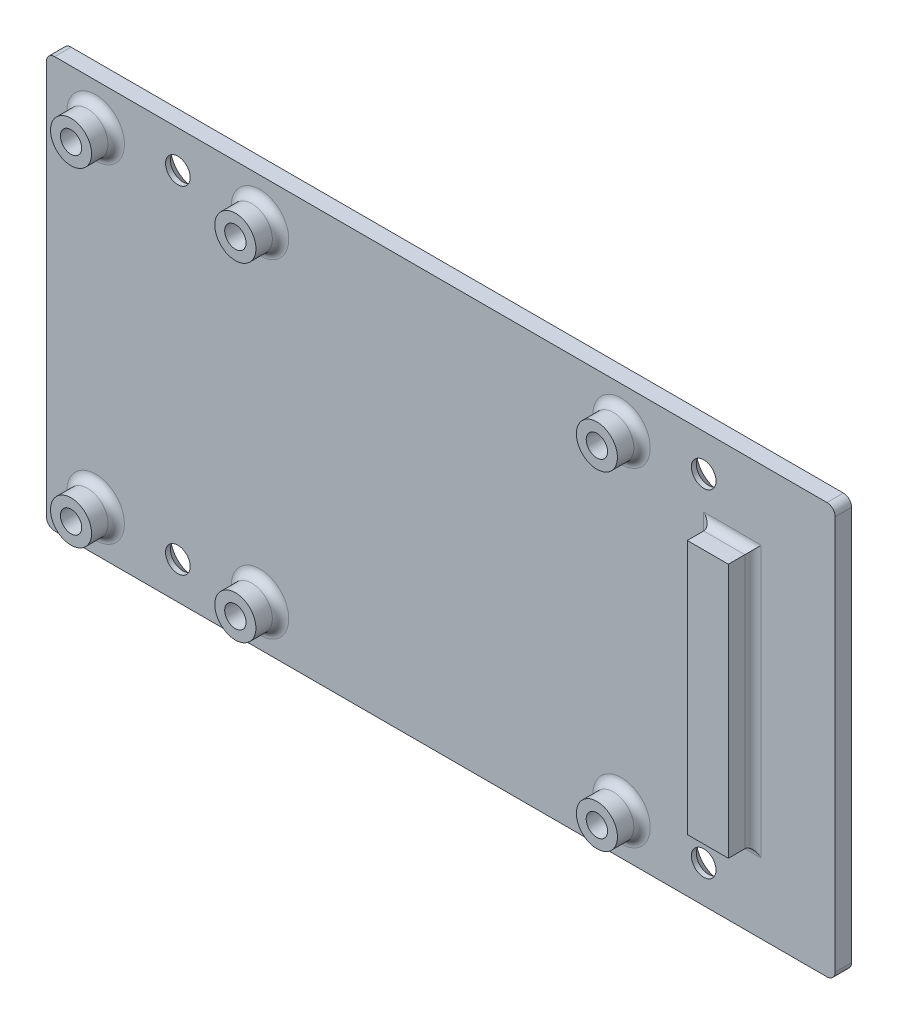
SolidWorks part; units mm, degrees
ref_plane "Спереди" through (0, 0, 0) normal (0, 0, 1) x (1, 0, 0)
ref_plane "Сверху" through (0, 0, 0) normal (0, 1, 0) x (1, 0, 0)
ref_plane "Справа" through (0, 0, 0) normal (1, 0, 0) x (0, 0, -1)
sketch "Эскиз1" plane through (0, 0, 60.7538) normal (0, 0, -1) x (-1, 0, 0)
  line L0 (-84.5501, 64.5438) -> (-84.5501, 29.5438)
  line L17 (-1.5112, 29.1447) -> (-7.5891, 29.1447)
  line L18 (-9.3198, 24.0438) -> (-63.7804, 24.0438)
  line L19 (-73.3198, 24.0438) -> (-82.5501, 24.0438)
  line L20 (-82.5501, 24.0438) -> (-82.5501, 29.5438)
  line L21 (-82.5501, 29.5438) -> (-84.5501, 29.5438)
  line L22 (-84.5501, 29.5438) -> (-84.5501, 23.0438)
  line L23 (-83.5501, 22.0438) -> (10.4499, 22.0438)
  line L24 (11.4499, 23.0438) -> (11.4499, 71.0438)
  line L25 (10.4499, 72.0438) -> (-83.5501, 72.0438)
  line L26 (-84.5501, 71.0438) -> (-84.5501, 64.5438)
  line L27 (-84.5501, 64.5438) -> (-82.5501, 64.5438)
  line L28 (-82.5501, 64.5438) -> (-82.5501, 70.0438)
  line L29 (-82.5501, 70.0438) -> (-73.3198, 70.0438)
  line L31 (0.2196, 70.0438) -> (9.4499, 70.0438)
  line L32 (9.4499, 70.0438) -> (9.4499, 24.0438)
  line L33 (9.4499, 24.0438) -> (0.2196, 24.0438)
  line L35 (-63.7804, 70.0438) -> (-9.3198, 70.0438)
  line L39 (-84.5501, 29.5438) -> (-84.5501, 23.0438)
  line L40 (-83.5501, 22.0438) -> (10.4499, 22.0438)
  line L41 (11.4499, 23.0438) -> (11.4499, 71.0438)
  line L42 (10.4499, 72.0438) -> (-83.5501, 72.0438)
  line L43 (-84.5501, 71.0438) -> (-84.5501, 64.5438)
  circle A0 centre (-4.5501, 67.5438) radius 1.5
  circle A1 centre (-68.5501, 67.5438) radius 1.5
  circle A2 centre (-68.5501, 26.5438) radius 1.5
  circle A3 centre (-4.5501, 26.5438) radius 1.5
  arc A9 (-0.7344, 25.3438) -> (-1.5112, 29.1447) centre (-4.5501, 26.5438) ccw
  arc A10 (-7.5891, 29.1447) -> (-8.3659, 25.3438) centre (-4.5501, 26.5438) ccw
  arc A11 (-64.7344, 25.3438) -> (-72.3659, 25.3438) centre (-68.5501, 26.5438) ccw
  arc A12 (-84.5501, 23.0438) -> (-83.5501, 22.0438) centre (-83.5501, 23.0438) ccw
  arc A13 (10.4499, 22.0438) -> (11.4499, 23.0438) centre (10.4499, 23.0438) ccw
  arc A14 (11.4499, 71.0438) -> (10.4499, 72.0438) centre (10.4499, 71.0438) ccw
  arc A15 (-83.5501, 72.0438) -> (-84.5501, 71.0438) centre (-83.5501, 71.0438) ccw
  arc A16 (-72.3659, 68.7438) -> (-64.7344, 68.7438) centre (-68.5501, 67.5438) ccw
  arc A17 (-8.3659, 68.7438) -> (-0.7344, 68.7438) centre (-4.5501, 67.5438) ccw
  arc A21 (-84.5501, 23.0438) -> (-83.5501, 22.0438) centre (-83.5501, 23.0438) ccw
  arc A22 (10.4499, 22.0438) -> (11.4499, 23.0438) centre (10.4499, 23.0438) ccw
  arc A23 (11.4499, 71.0438) -> (10.4499, 72.0438) centre (10.4499, 71.0438) ccw
  arc A24 (-83.5501, 72.0438) -> (-84.5501, 71.0438) centre (-83.5501, 71.0438) ccw
  arc A34 (-9.3198, 24.0438) -> (-8.3659, 25.3438) centre (-9.3198, 25.0438) ccw
  arc A36 (-64.7344, 25.3438) -> (-63.7804, 24.0438) centre (-63.7804, 25.0438) ccw
  arc A38 (-73.3198, 24.0438) -> (-72.3659, 25.3438) centre (-73.3198, 25.0438) ccw
  arc A40 (-72.3659, 68.7438) -> (-73.3198, 70.0438) centre (-73.3198, 69.0438) ccw
  arc A42 (-63.7804, 70.0438) -> (-64.7344, 68.7438) centre (-63.7804, 69.0438) ccw
  arc A44 (-8.3659, 68.7438) -> (-9.3198, 70.0438) centre (-9.3198, 69.0438) ccw
  arc A46 (0.2196, 70.0438) -> (-0.7344, 68.7438) centre (0.2196, 69.0438) ccw
  arc A48 (-0.7344, 25.3438) -> (0.2196, 24.0438) centre (0.2196, 25.0438) ccw
  dimension "D2" = 3
  dimension "D1" = 0
extrude "Бобышка-Вытянуть2" add sketch "Эскиз1" along normal blind 2
chamfer "Фаска1" distance 1.4 angle 45 4 edges at (67.0501, 26.5438, 58.7538) (3.0501, 26.5438, 58.7538) (3.0501, 67.5438, 58.7538) (67.0501, 67.5438, 58.7538)
sketch "Эскиз2" plane through (0, 0, 60.7538) normal (0, 0, 1) x (1, 0, 0)
  line L0 (78.3302, 72.0438) -> (78.3302, 22.0438) construction
  line L1 (-10.4499, 72.0438) -> (83.5501, 72.0438) construction
  line L2 (83.5501, 22.0438) -> (-10.4499, 22.0438) construction
sketch "Эскиз3" plane through (0, 0, 60.7538) normal (0, 0, 1) x (1, 0, 0)
  line L0 (71.6726, 70.0438) -> (82.5501, 70.0438) construction
  line L1 (69.5501, 62.5438) -> (74.5501, 62.5438)
  line L2 (69.5501, 62.5438) -> (69.5501, 31.5438)
  line L3 (69.5501, 31.5438) -> (74.5501, 31.5438)
  line L4 (74.5501, 62.5438) -> (74.5501, 31.5438)
  line L5 (82.5501, 24.0438) -> (71.6726, 24.0438) construction
  line L6 (82.5501, 70.0438) -> (82.5501, 24.0438) construction
  line L7 (-11.4499, 47.0438) -> (84.5501, 47.0438) construction
  line L8 (-11.4499, 23.0438) -> (-11.4499, 71.0438) construction
  line L9 (84.5501, 71.0438) -> (84.5501, 23.0438) construction
  line L10 (36.5501, 72.0438) -> (36.5501, 22.0438) construction
  line L11 (-10.4499, 72.0438) -> (83.5501, 72.0438) construction
  line L12 (83.5501, 22.0438) -> (-10.4499, 22.0438) construction
  line L13 (-11.4499, 67.0438) -> (62.6459, 67.0438) construction
  line L14 (14.5501, 22.0438) -> (14.5501, 72.0438) construction
  line L15 (-5.4499, 72.0438) -> (-5.4499, 22.0438) construction
  circle A0 centre (14.5501, 67.0438) radius 2.5
  circle A1 centre (14.5501, 67.0438) radius 1.3
  circle A2 centre (58.5501, 67.0438) radius 1.3
  circle A3 centre (58.5501, 67.0438) radius 2.5
  circle A4 centre (58.5501, 27.0438) radius 1.3
  circle A5 centre (58.5501, 27.0438) radius 2.5
  circle A6 centre (14.5501, 27.0438) radius 1.3
  circle A7 centre (14.5501, 27.0438) radius 2.5
  arc A8 (1.4276, 70.0438) -> (7.6726, 70.0438) centre (4.5501, 67.5438) ccw construction
  circle A9 centre (-5.4499, 67.0438) radius 2.5
  circle A10 centre (-5.4499, 67.0438) radius 1.3
  circle A11 centre (-5.4499, 27.0438) radius 1.3
  circle A12 centre (-5.4499, 27.0438) radius 2.5
  dimension "D7" = 5
  dimension "D8" = 2.6
  dimension "D1" = 7.5
  dimension "D2" = 7.5
  dimension "D3" = 5
  dimension "D4" = 8
  dimension "D5" = 5
  dimension "D6" = 22
  dimension "D9" = 10
extrude "Бобышка-Вытянуть3" add sketch "Эскиз3" along normal blind 3
fillet "Скругление1" radius 1 10 edges at (72.0501, 31.5438, 60.7538) (69.5501, 47.0438, 60.7538) (72.0501, 62.5438, 60.7538) (74.5501, 47.0438, 60.7538) (-7.9499, 27.0438, 60.7538) (12.0501, 27.0438, 60.7538) (56.0501, 27.0438, 60.7538) (56.0501, 67.0438, 60.7538) (12.0501, 67.0438, 60.7538) (-7.9499, 67.0438, 60.7538)
